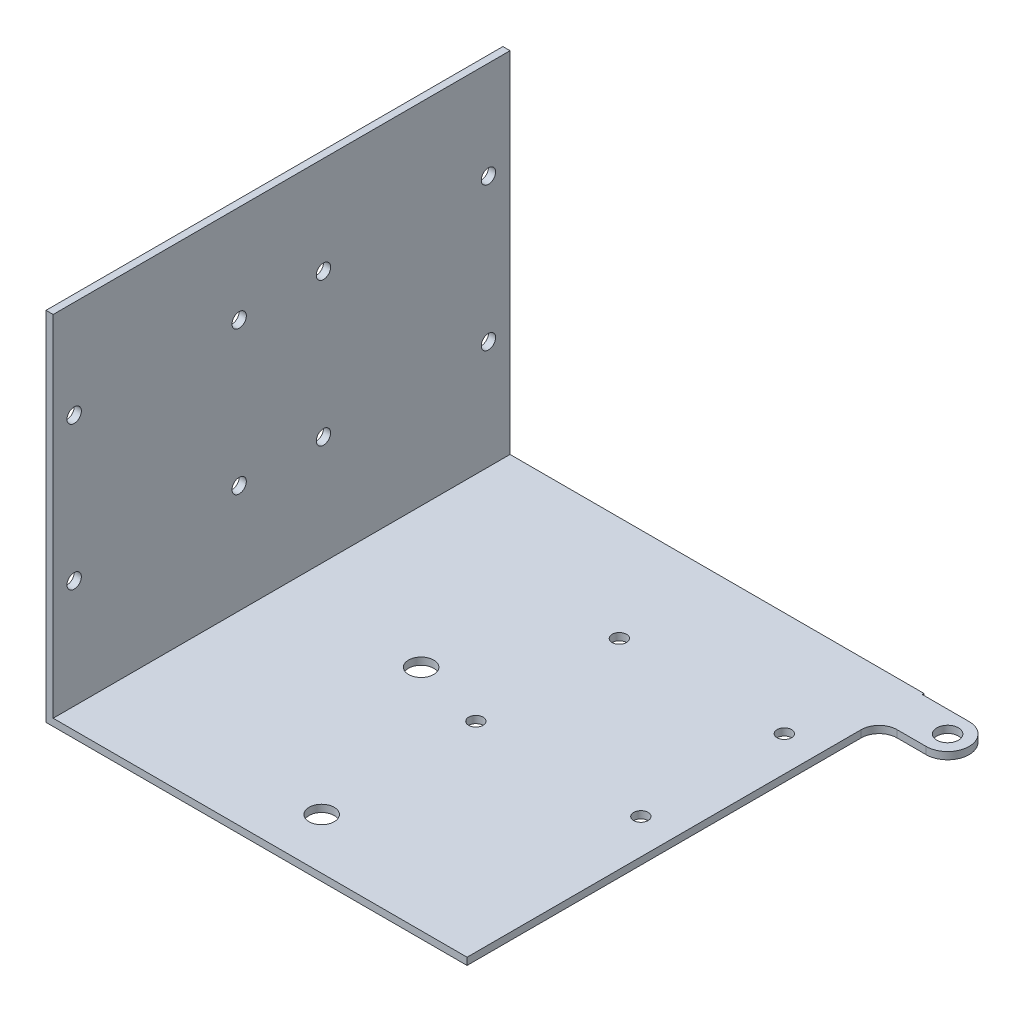
SolidWorks part; units mm, degrees
ref_plane "Спереди" through (0, 0, 0) normal (0, 0, 1) x (1, 0, 0)
ref_plane "Сверху" through (0, 0, 0) normal (0, 1, 0) x (1, 0, 0)
ref_plane "Справа" through (0, 0, 0) normal (1, 0, 0) x (0, 0, -1)
sketch "Эскиз1" plane through (0, 0, 0) normal (1, 0, 0) x (0, 0, -1)
  line L0 (63.696, 69.8758) -> (-63.696, 69.8758)
  line L1 (-0.0869, 69.8758) -> (-0.0869, -69.8758) construction
  line L2 (63.696, -29.624) -> (-63.696, -29.624)
  line L3 (63.696, 69.8758) -> (63.696, -29.624)
  line L4 (-63.696, 69.8758) -> (-63.696, -29.624)
  circle A0 centre (11.6631, 42.626) radius 2
  circle A1 centre (57.6631, 42.626) radius 2
  circle A2 centre (57.6631, 2.626) radius 2
  circle A3 centre (11.6631, 2.626) radius 2
  circle A4 centre (-11.8369, 2.626) radius 2
  circle A5 centre (-57.8369, 2.626) radius 2
  circle A6 centre (-57.8369, 42.626) radius 2
  circle A7 centre (-11.8369, 42.626) radius 2
extrude "Бобышка-Вытянуть1" add sketch "Эскиз1" along normal blind 2
sketch "Эскиз2" plane through (2, 0, 0) normal (1, 0, 0) x (0, 0, -1)
  line L0 (63.696, -29.624) -> (63.696, 69.8758) construction
  line L1 (-63.696, -29.624) -> (63.696, -29.624)
  line L2 (-63.696, -29.624) -> (-63.696, -27.624)
  line L3 (-63.696, -27.624) -> (63.696, -27.624)
  line L4 (63.696, -29.624) -> (63.696, -27.624)
  dimension "D1" = 2
extrude "Бобышка-Вытянуть2" add sketch "Эскиз2" along normal blind 115.4
sketch "Эскиз4" plane through (0, 21.676, 0) normal (0, 1, 0) x (1, 0, 0)
  circle A0 centre (61.65, 34.5126) radius 2
  circle A1 centre (61.65, -5.4874) radius 2
  circle A2 centre (107.65, -5.4874) radius 2
  circle A3 centre (107.65, 34.5126) radius 2
extrude "Вырез-Вытянуть1" cut sketch "Эскиз4" against normal through all
sketch "Эскиз6" plane through (0, -27.624, 0) normal (0, 1, 0) x (1, 0, 0)
  line L0 (77.8375, -49.504) -> (47.5024, -49.504) construction
  line L1 (40.9798, -10.8906) -> (41.0012, 10.7183) construction
  circle A0 centre (62.67, -49.504) radius 3.5
  circle A1 centre (40.9905, -0.0862) radius 3.5
extrude "Вырез-Вытянуть2" cut sketch "Эскиз6" against normal through all
sketch "Эскиз7" plane through (0, -27.624, 0) normal (0, 1, 0) x (1, 0, 0)
  line L0 (130.5, 51.196) -> (117.4, 51.196)
  line L1 (117.4, 63.696) -> (117.4, -63.696) construction
  line L2 (130.5, 63.196) -> (117.4, 63.196)
  line L3 (117.4, 63.196) -> (117.4, 51.196)
  circle A0 centre (130.5, 57.196) radius 3
  arc A1 (130.5, 51.196) -> (130.5, 63.196) centre (130.5, 57.196) ccw
  circle A2 centre (130.5, 57.196) radius 6 construction
  dimension "D1" = 3
extrude "Бобышка-Вытянуть3" add sketch "Эскиз7" against normal blind 2
fillet "Скругление1" radius 5 1 edges at (117.4, -28.624, -51.196)
ref_plane "Плоскость4" through (-15, 0, 0) normal (-1, 0, 0) x (0, 0, 1)
